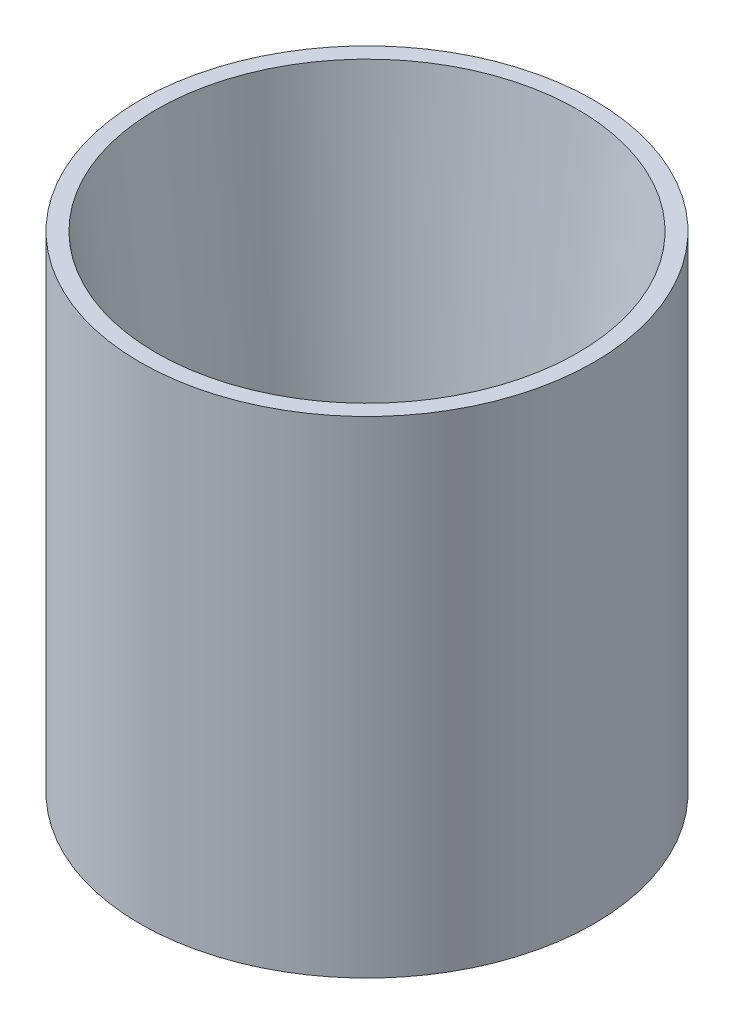
SolidWorks part; units mm, degrees
ref_plane "Front Plane" through (0, 0, 0) normal (0, 0, 1) x (1, 0, 0)
ref_plane "Top Plane" through (0, 0, 0) normal (0, 1, 0) x (1, 0, 0)
ref_plane "Right Plane" through (0, 0, 0) normal (1, 0, 0) x (0, 0, -1)
sketch "Sketch1" plane through (0, 0, 0) normal (0, 0, 1) x (1, 0, 0)
  line L4 (-19.7152, -16.6452) -> (-21.7971, -16.6452)
  line L9 (-14.7971, 26.4248) -> (-14.7971, -17.3951) construction
  line L12 (-21.7971, -3.1452) -> (-21.7971, -16.6452)
  line L14 (-21.7971, -3.1452) -> (-21.7971, -1.6452)
  line L15 (-21.7971, -1.6452) -> (-21.2971, -1.6452)
  line L16 (-19.7152, -16.6452) -> (-19.7152, -16.1452)
  line L17 (-19.7152, -16.1452) -> (-21.2971, -1.6452)
  point P12 (-25.6121, 21.3263)
  dimension "D1" = 0.5
  dimension "D2" = 0.5
  dimension "D3" = 13.5
  dimension "D4" = 1.5
revolve "Revolve1" add sketch "Sketch1" angle 360 about L9
